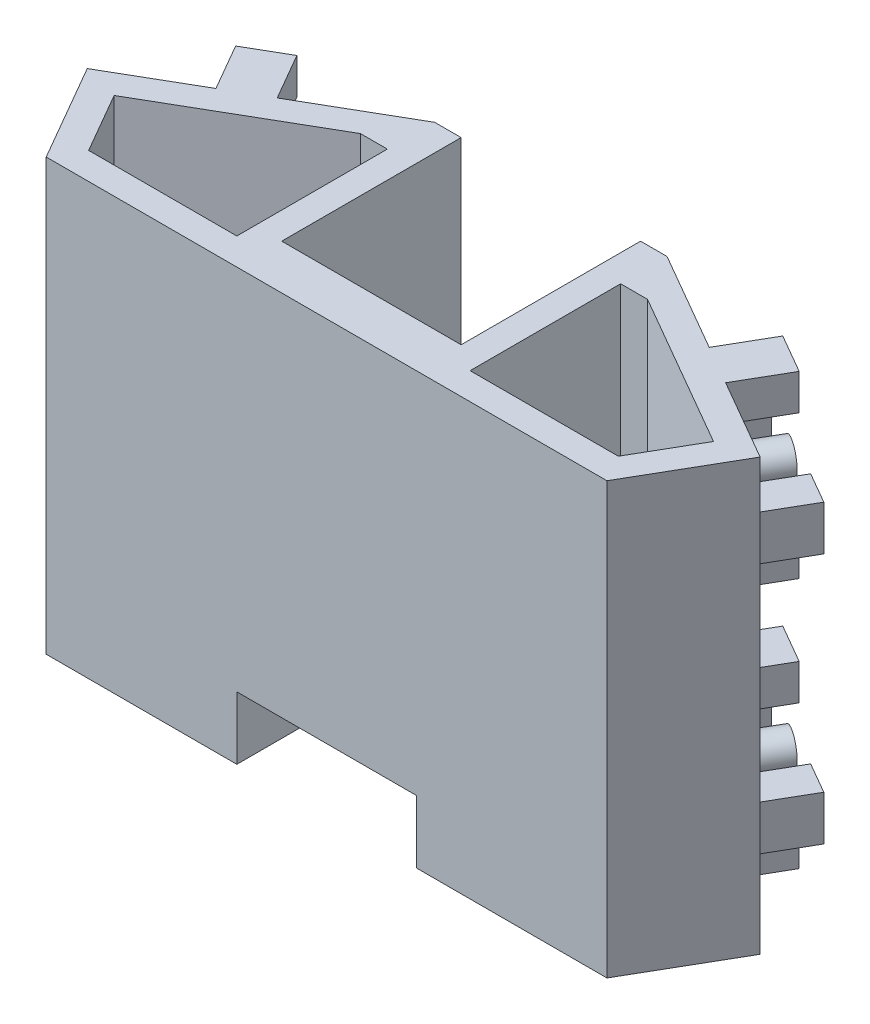
SolidWorks part; units mm, degrees
ref_plane "Plan de face" through (0, 0, 0) normal (0, 0, 1) x (1, 0, 0)
ref_plane "Plan de dessus" through (0, 0, 0) normal (0, 1, 0) x (1, 0, 0)
ref_plane "Plan de droite" through (0, 0, 0) normal (1, 0, 0) x (0, 0, -1)
sketch "Esquisse1" plane through (0, 0, 0) normal (0, 1, 0) x (1, 0, 0)
  line L0 (-31.25, 0) -> (31.25, 0)
  line L1 (31.25, 0) -> (37.5, 10.8253)
  line L2 (37.5, 10.8253) -> (12.9487, 25)
  line L3 (12.9487, 25) -> (10, 25)
  line L4 (10, 25) -> (10, 5)
  line L5 (10, 5) -> (-10, 5)
  line L6 (-10, 5) -> (-10, 25)
  line L7 (-10, 25) -> (-12.9487, 25)
  line L8 (-12.9487, 25) -> (-37.5, 10.8253)
  line L9 (-37.5, 10.8253) -> (-31.25, 0)
  line L10 (0, 5) -> (0, 0) construction
  dimension "D1" = 120
  dimension "D2" = 5
  dimension "D3" = 20
  dimension "D4" = 62.5
  dimension "D5" = 12.5
extrude "Boss.-Extru.1" add sketch "Esquisse1" along normal blind 48
sketch "Esquisse2" plane through (0, 48, 0) normal (0, 1, 0) x (1, 0, 0)
  line L0 (-36, 8.2272) -> (-16, 19.7742)
  line L1 (-16, 19.7742) -> (-13, 19.7742)
  line L3 (-37.5, 10.8253) -> (-12.9487, 25) construction
  line L4 (-31.25, 0) -> (-37.5, 10.8253) construction
  line L6 (-13, 19.7742) -> (-13, 0)
  line L7 (31.25, 0) -> (-31.25, 0) construction
  line L8 (-13, 0) -> (-31.25, 0)
  line L9 (-31.25, 0) -> (-36, 8.2272)
  line L10 (-10, 25) -> (-10, 5) construction
  dimension "D1" = 3
  dimension "D2" = 3
  dimension "D3" = 3
extrude "Enlèv. mat.-Extru.1" cut sketch "Esquisse2" against normal up to next
mirror "Symétrie1" about plane through (0, 0, 0) normal (1, 0, 0) of "Enlèv. mat.-Extru.1"
sketch "Esquisse3" plane through (-14.0625, 0, -24.357) normal (0.5, 0, 0.866) x (0.866, 0, -0.5)
  line L0 (-27.0633, 48) -> (-27.0633, 0) construction
  line L4 (-3.9693, 48) -> (-27.0633, 48) construction
  line L5 (-14.0633, 44) -> (-14.0633, 32) construction
  line L6 (-11.5633, 48) -> (-16.5633, 48)
  line L7 (-11.5633, 48) -> (-11.5633, 44)
  line L8 (-11.5633, 44) -> (-16.5633, 44)
  line L9 (-16.5633, 48) -> (-16.5633, 44)
  line L10 (-20.0633, 40.5) -> (-24.0633, 40.5)
  line L11 (-20.0633, 40.5) -> (-20.0633, 35.5)
  line L12 (-20.0633, 35.5) -> (-24.0633, 35.5)
  line L13 (-24.0633, 40.5) -> (-24.0633, 35.5)
  line L14 (-4.0633, 40.5) -> (-8.0633, 40.5)
  line L15 (-4.0633, 40.5) -> (-4.0633, 35.5)
  line L16 (-4.0633, 35.5) -> (-8.0633, 35.5)
  line L17 (-8.0633, 40.5) -> (-8.0633, 35.5)
  line L18 (-11.5633, 32) -> (-16.5633, 32)
  line L19 (-11.5633, 32) -> (-11.5633, 28)
  line L20 (-11.5633, 28) -> (-16.5633, 28)
  line L21 (-16.5633, 32) -> (-16.5633, 28)
  line L23 (-8.0633, 38) -> (-20.0633, 38) construction
  circle A1 centre (-14.0633, 38) radius 1.9
  dimension "D1" = 5
  dimension "D2" = 4
  dimension "D3" = 10
  dimension "D4" = 3.8
  dimension "D5" = 20
  dimension "D6" = 13
sketch "Esquisse4" plane through (0, 0, 0) normal (0, 1, 0) x (1, 0, 0)
  line L0 (-37.5, 10.8253) -> (-31.25, 0)
  line L1 (-31.25, 0) -> (31.25, 0)
  line L2 (31.25, 0) -> (37.5, 10.8253)
  line L3 (12.9487, 25) -> (37.5, 10.8253) construction
  line L4 (37.5, 10.8253) -> (36, 8.2272) construction
  line L5 (-36, 8.2272) -> (-37.5, 10.8253) construction
  line L6 (-37.5, 10.8253) -> (-34.9019, 12.3253)
  line L7 (-37.5, 10.8253) -> (-12.9487, 25) construction
  line L8 (-34.9019, 12.3253) -> (-29.5179, 3)
  line L9 (-29.5179, 3) -> (29.5179, 3)
  line L10 (29.5179, 3) -> (34.9019, 12.3253)
  line L11 (34.9019, 12.3253) -> (37.5, 10.8253)
  line L12 (0, 0) -> (0, 3) construction
  dimension "D1" = 3
extrude "Boss.-Extru.2" add sketch "Esquisse4" along normal up to surface (48 mm away) up to face at (0, 48, -14.2001)
extrude "Boss.-Extru.3" add sketch "Esquisse3" against normal blind 6
ref_plane "Plan1" through (0, 24, 0) normal (0, 1, 0) x (1, 0, 0)
mirror "Symétrie2" about plane through (0, 24, 0) normal (0, 1, 0) of "Boss.-Extru.3"
mirror "Symétrie3" about plane through (0, 0, 0) normal (1, 0, 0) of "Symétrie2", "Boss.-Extru.3"
sketch "Esquisse5" plane through (0, 0, 0) normal (0, 1, 0) x (1, 0, 0)
  line L0 (31.25, 0) -> (-31.25, 0) construction
  line L1 (-10, 5) -> (10, 5)
  line L2 (-10, 5) -> (-10, 0)
  line L3 (-10, 0) -> (10, 0)
  line L4 (10, 5) -> (10, 0)
  line L5 (10, 5) -> (10, 25) construction
extrude "Enlèv. mat.-Extru.2" cut sketch "Esquisse5" along normal blind 7
